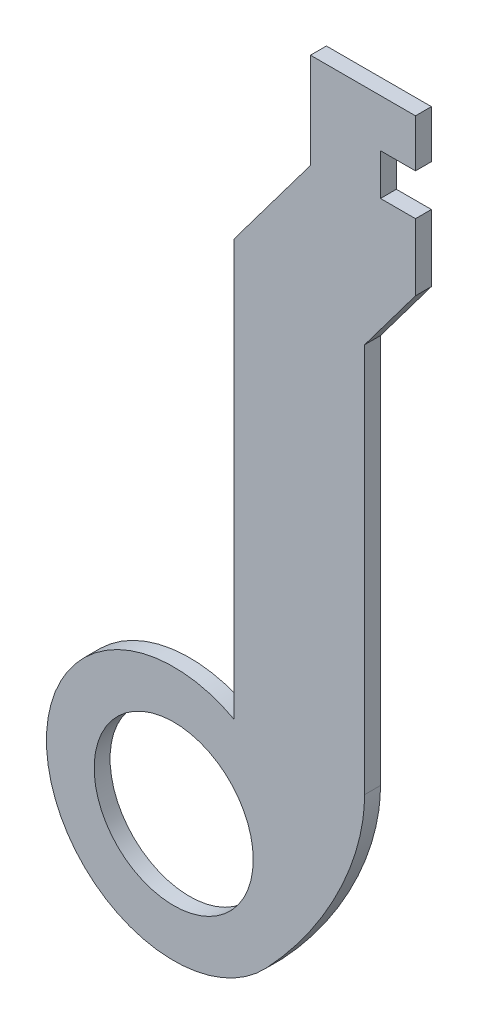
SolidWorks part; units mm, degrees
ref_plane "Alzado" through (0, 0, 0) normal (0, 0, 1) x (1, 0, 0)
ref_plane "Planta" through (0, 0, 0) normal (0, 1, 0) x (1, 0, 0)
ref_plane "Vista lateral" through (0, 0, 0) normal (1, 0, 0) x (0, 0, -1)
sketch "Croquis1" plane through (0, 0, 0) normal (0, 0, 1) x (1, 0, 0)
  line L1 (0, 0) -> (0, -1.5)
  line L2 (0, -1.5) -> (-1.1, -1.5)
  line L3 (-1.1, -1.5) -> (-1.1, -2.8)
  line L4 (-1.1, -2.8) -> (0, -2.8)
  line L5 (0, -2.8) -> (0, -4.9)
  line L6 (0, -4.9) -> (-1.6, -7.0333)
  line L9 (-5.7, -19.2801) -> (-5.7, -6.2)
  line L10 (-5.7, -6.2) -> (-3.3, -3)
  line L11 (-3.3, -3) -> (-3.3, 0)
  line L13 (-3.3, 0) -> (0, 0)
  line L14 (-1.6, -7.0333) -> (-1.6, -19.2801)
  line L16 (-7.6, -22.8) -> (-11.6, -22.8) construction
  line L17 (-7.6, -26.8) -> (-1.6, -26.8) construction
  line L18 (-1.6, -19.2801) -> (-1.6, -26.8) construction
  line L19 (-5.7, -19.2801) -> (-1.6, -19.2801) construction
  arc A0 (-5.7, -19.2801) -> (-4.6956, -25.5504) centre (-7.6, -22.8) ccw
  ellipse E0 centre (-7.6, -22.8) end of major axis (-2.3498, -17.2559) minor radius 4 (-4.6956, -25.5504) -> (-1.6, -19.2801) ccw
  dimension "D1" = 3.3
  dimension "D10" = 6.2
  dimension "D11" = 8
  dimension "D2" = 1.5
  dimension "D3" = 2.2
  dimension "D4" = 1.3
  dimension "D5" = 3
  dimension "D6" = 5.7
  dimension "D7" = 26.8
  dimension "D8" = 2.1
  dimension "D9" = 4.1
  dimension "D12" = 10
extrude "Saliente-Extruir1" add sketch "Croquis1" along normal blind 0.5
sketch "Croquis6" plane through (0, 0, 0.5) normal (0, 0, 1) x (1, 0, 0)
  circle A0 centre (-7.6, -22.8) radius 2.5
  dimension "D1" = 5
extrude "Cortar-Extruir6" cut sketch "Croquis6" against normal up to next
